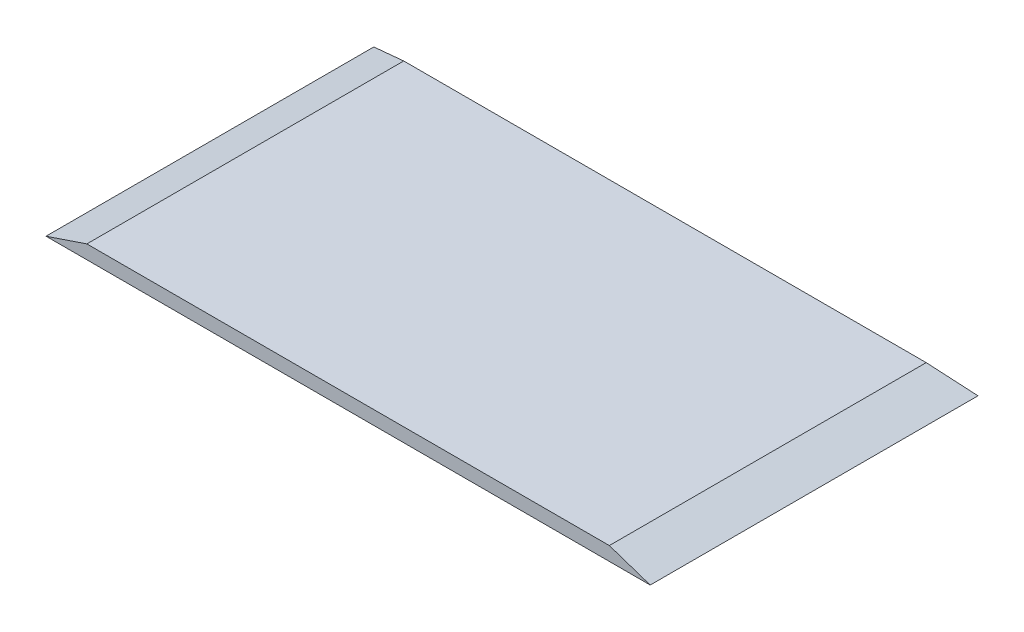
SolidWorks part; units mm, degrees
ref_plane "Plano frontal" through (0, 0, 0) normal (0, 0, 1) x (1, 0, 0)
ref_plane "Plano superior" through (0, 0, 0) normal (0, 1, 0) x (1, 0, 0)
ref_plane "Plano direito" through (0, 0, 0) normal (1, 0, 0) x (0, 0, -1)
sketch "Esboço1" plane through (0, 0, 0) normal (0, 1, 0) x (1, 0, 0)
  line L1 (0, 0) -> (55.3, 0)
  line L2 (0, 0) -> (0, 30)
  line L3 (0, 30) -> (55.3, 30)
  line L4 (55.3, 0) -> (55.3, 30)
  dimension "D1" = 55.3
  dimension "D2" = 30
extrude "Ressalto-extrusão1" add sketch "Esboço1" along normal blind 1.26
sketch "Esboço2" plane through (0, 0, 0) normal (-1, 0, 0) x (0, 0, 1)
  line L0 (-30, 0) -> (-29, 1.26)
  line L1 (-30, 1.26) -> (0, 1.26) construction
  line L2 (-29, 1.26) -> (-30, 1.26)
  line L3 (-30, 1.26) -> (-30, 0)
  dimension "D1" = 1
extrude "Corte-extrusão1" cut sketch "Esboço2" against normal through all
sketch "Esboço3" plane through (0, 0, 0) normal (0, 0, 1) x (1, 0, 0)
  line L0 (0, 0) -> (3.74, 1.26)
  line L1 (0, 1.26) -> (55.3, 1.26) construction
  line L2 (55.3, 1.26) -> (51.56, 1.26)
  line L4 (55.3, 0) -> (55.3, 1.26)
  line L5 (0, 0) -> (-0.0011, 0.0384)
  line L6 (27.65, 1.26) -> (27.65, 16.8293) construction
  line L7 (0, 0) -> (0, 1.26)
  line L8 (0, 1.26) -> (3.74, 1.26)
  line L9 (55.3, 0) -> (55.3011, 0.0384)
  line L10 (55.3, 0) -> (51.56, 1.26)
  line M5 (55.3, 0) -> (55.3, 1.26)
  line M6 (55.3, 1.26) -> (0, 1.26)
  line M7 (0, 1.26) -> (0, 0)
  dimension "D1" = 3.74
extrude "Corte-extrusão2" cut sketch "Esboço3" against normal through all contours L0 M7 M6 | L10 M5 M6
